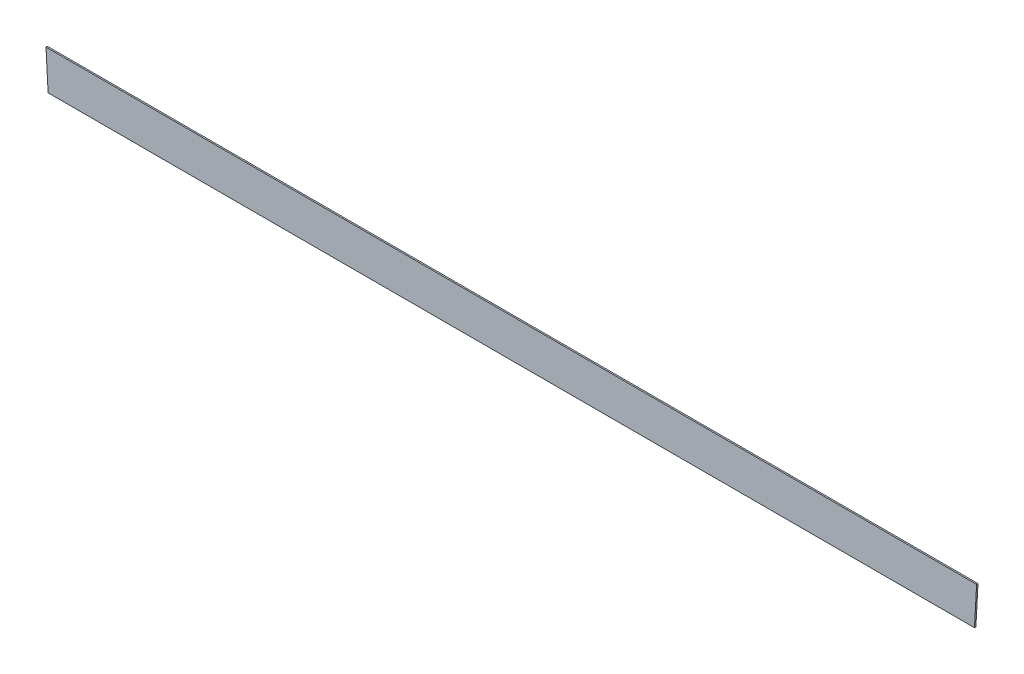
SolidWorks part; units mm, degrees
ref_plane "Front Plane" through (0, 0, 0) normal (0, 0, 1) x (1, 0, 0)
ref_plane "Top Plane" through (0, 0, 0) normal (0, 1, 0) x (1, 0, 0)
ref_plane "Right Plane" through (0, 0, 0) normal (1, 0, 0) x (0, 0, -1)
sketch "Sketch1" plane through (0, 0, 0) normal (0, 0, 1) x (1, 0, 0)
  line L0 (-660.5, 27.5) -> (-663.5, 27.5)
  line L1 (-660.5, -27.5) -> (660.5, -27.5)
  line L2 (-660.5, -27.5) -> (-660.5, 27.5) construction
  line L3 (-660.5, 27.5) -> (660.5, 27.5)
  line L4 (660.5, -27.5) -> (660.5, 27.5) construction
  line L5 (-660.5, -27.5) -> (660.5, 27.5) construction
  line L6 (-660.5, 27.5) -> (660.5, -27.5) construction
  line L7 (-663.5, 27.5) -> (-660.5, -27.5)
  line L8 (660.5, 27.5) -> (663.5, 27.5)
  line L9 (663.5, 27.5) -> (660.5, -27.5)
  point P0 (0, 0)
  dimension "D1" = 1321
  dimension "D2" = 55
  dimension "D3" = 1327
extrude "Boss-Extrude1" add sketch "Sketch1" along normal blind 2
